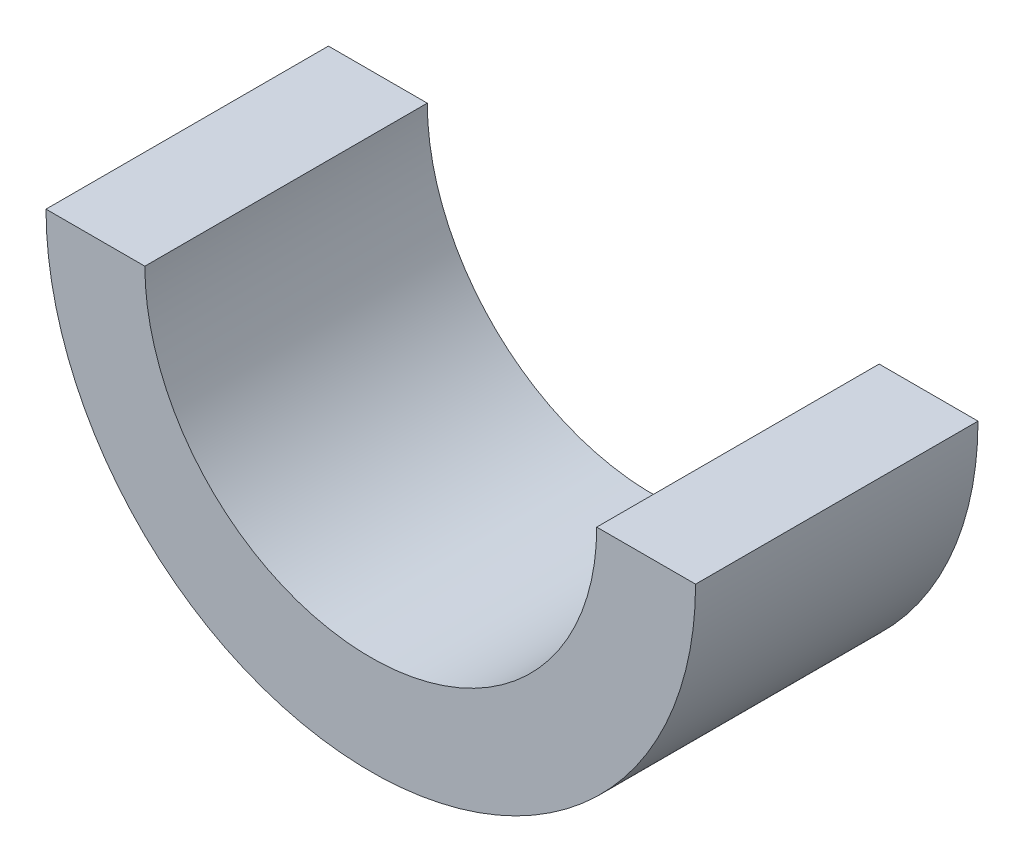
SolidWorks part; units mm, degrees
ref_plane "Front Plane" through (0, 0, 0) normal (0, 0, 1) x (1, 0, 0)
ref_plane "Top Plane" through (0, 0, 0) normal (0, 1, 0) x (1, 0, 0)
ref_plane "Right Plane" through (0, 0, 0) normal (1, 0, 0) x (0, 0, -1)
sketch "Sketch1" plane through (0, 0, 0) normal (0, 0, 1) x (1, 0, 0)
  line L0 (46, 23) -> (39, 23)
  line L1 (7, 23) -> (0, 23)
  arc A0 (0, 23) -> (46, 23) centre (23, 23) ccw
  arc A1 (39, 23) -> (7, 23) centre (23, 23) cw
  dimension "D1" = 23
  dimension "D2" = 16
extrude "Profile" add sketch "Sketch1" along normal blind 20
equation "\"Profile_Depth\"= 20mm"
equation "\"D1@Profile\" = \"Profile_Depth\""
equation "\"Profile_Sketch_1\"= 23mm"
equation "\"D1@Sketch1\" = \"Profile_Sketch_1\""
equation "\"Profile_Sketch_2\"= 16mm"
equation "\"D2@Sketch1\" = \"Profile_Sketch_2\""
equation "\"EnvelopeWidth\"= 46mm"
equation "\"EnvelopeHeight\"= 46mm"
